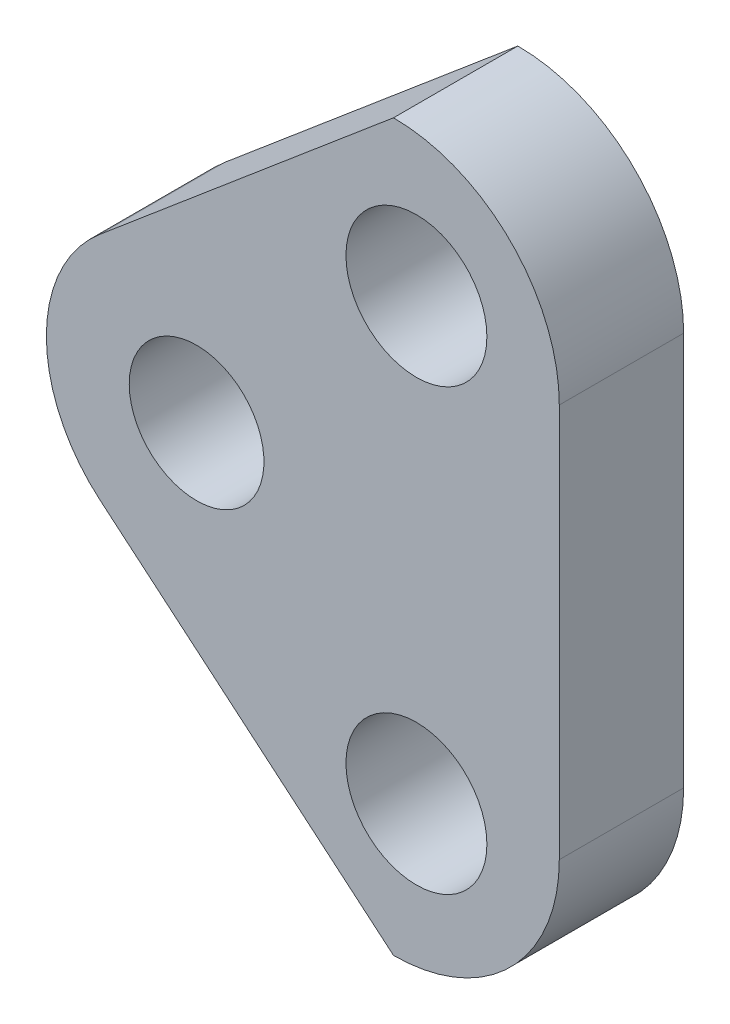
SolidWorks part; units mm, degrees
ref_plane "前视基准面" through (0, 0, 0) normal (0, 0, 1) x (1, 0, 0)
ref_plane "上视基准面" through (0, 0, 0) normal (0, 1, 0) x (1, 0, 0)
ref_plane "右视基准面" through (0, 0, 0) normal (1, 0, 0) x (0, 0, -1)
other "Configuration Table"
sketch "草图1" plane through (0, 0, 0) normal (0, 0, 1) x (1, 0, 0)
  line L1 (-9.5, -17.5) -> (9.5, -17.5)
  line L2 (-17.5, -9.5) -> (-17.5, 9.5)
  line L3 (-9.5, 17.5) -> (9.5, 17.5)
  line L4 (17.5, -9.5) -> (17.5, 9.5)
  line L5 (-17.5, -17.5) -> (17.5, 17.5) construction
  line L6 (-17.5, 17.5) -> (17.5, -17.5) construction
  circle A0 centre (0, 0) radius 15
  circle A1 centre (10.6066, 10.6066) radius 3.4
  circle A2 centre (10.6066, -10.6066) radius 3.4
  circle A3 centre (-10.6066, -10.6066) radius 3.4
  circle A4 centre (-10.6066, 10.6066) radius 3.4
  arc A5 (17.5, 9.5) -> (9.5, 17.5) centre (9.5, 9.5) ccw
  arc A6 (9.5, -17.5) -> (17.5, -9.5) centre (9.5, -9.5) ccw
  arc A7 (-9.5, -17.5) -> (-17.5, -9.5) centre (-9.5, -9.5) cw
  arc A8 (-17.5, 9.5) -> (-9.5, 17.5) centre (-9.5, 9.5) cw
  point P18 (0, 0)
  dimension "D1" = 30
  dimension "D2" = 6.8
  dimension "D6" = 8
  dimension "D3" = 35
  dimension "D4" = 35
  dimension "D5" = 4
extrude "凸台-拉伸1" add sketch "草图1" along normal blind 11 contours A4 A0 A3 A2 A1 | A8 L2 A7 L1 A6 L4 A5 L3 A4 A0 A1 A2 A3
sketch "草图2" plane through (0, 0, 0) normal (0, 0, -1) x (-1, 0, 0)
  circle A0 centre (10.6066, -10.6066) radius 3.4 construction
  circle A1 centre (-10.6066, -10.6066) radius 3.4 construction
  circle A2 centre (10.6066, 10.6066) radius 3.4 construction
  circle A3 centre (-10.6066, 10.6066) radius 3.4 construction
  circle A4 centre (10.6066, -10.6066) radius 3.4
  circle A5 centre (-10.6066, -10.6066) radius 3.4
  circle A6 centre (10.6066, 10.6066) radius 3.4
  circle A7 centre (-10.6066, 10.6066) radius 3.4
extrude "凸台-拉伸2" add sketch "草图2" against normal blind 3
sketch "草图3" plane through (0, 0, 11) normal (0, 0, 1) x (1, 0, 0)
  circle A0 centre (0, 0) radius 3.4
  dimension "D1" = 6.8
extrude "切除-拉伸1" cut sketch "草图3" against normal through all
sketch "草图4" plane through (0, 0, 0) normal (0, 0, -1) x (-1, 0, 0)
  circle A0 centre (0, 0) radius 6
  circle A1 centre (0, 0) radius 3.4 construction
  circle A2 centre (0, 0) radius 3.4
  dimension "D1" = 12
extrude "切除-拉伸2" cut sketch "草图4" against normal blind 5
sketch "草图6" plane through (0, 0, 0) normal (0, 0, -1) x (-1, 0, 0)
  line L0 (0, 17.5) -> (17.5, 0)
  line L1 (9.5, 17.5) -> (-9.5, 17.5) construction
  line L2 (17.5, -9.5) -> (17.5, 9.5) construction
  line L3 (17.5, 0) -> (0, -17.5)
  line L4 (9.5, -17.5) -> (-9.5, -17.5) construction
  line L9 (9.5, 17.5) -> (-9.5, 17.5)
  line L10 (-17.5, 9.5) -> (-17.5, -9.5)
  line L11 (-9.5, -17.5) -> (9.5, -17.5)
  line L12 (17.5, -9.5) -> (17.5, 9.5)
  line L13 (9.5, 17.5) -> (-9.5, 17.5)
  line L14 (-17.5, 9.5) -> (-17.5, -9.5)
  line L15 (-9.5, -17.5) -> (9.5, -17.5)
  line L16 (17.5, -9.5) -> (17.5, 9.5)
  arc A4 (17.5, 9.5) -> (9.5, 17.5) centre (9.5, 9.5) ccw
  arc A5 (-9.5, 17.5) -> (-17.5, 9.5) centre (-9.5, 9.5) ccw
  arc A6 (-17.5, -9.5) -> (-9.5, -17.5) centre (-9.5, -9.5) ccw
  arc A7 (9.5, -17.5) -> (17.5, -9.5) centre (9.5, -9.5) ccw
  arc A8 (17.5, 9.5) -> (9.5, 17.5) centre (9.5, 9.5) ccw
  arc A9 (-9.5, 17.5) -> (-17.5, 9.5) centre (-9.5, 9.5) ccw
  arc A10 (-17.5, -9.5) -> (-9.5, -17.5) centre (-9.5, -9.5) ccw
  arc A11 (9.5, -17.5) -> (17.5, -9.5) centre (9.5, -9.5) ccw
  arc M10 (17.5, 9.5) -> (9.5, 17.5) centre (9.5, 9.5) ccw
  line M11 (9.5, 17.5) -> (-9.5, 17.5)
  line M15 (-9.5, -17.5) -> (9.5, -17.5)
  arc M16 (9.5, -17.5) -> (17.5, -9.5) centre (9.5, -9.5) ccw
  line M17 (17.5, -9.5) -> (17.5, 9.5)
  dimension "D1" = 0
extrude "切除-拉伸3" cut sketch "草图6" against normal through all contours L0 M11 M17 M10 | L3 M17 M15 M16
sketch "草图7" plane through (0, 0, 11) normal (0, 0, 1) x (1, 0, 0)
  line L0 (17.5, -9.5) -> (17.5, 9.5) construction
  line L6 (0, -17.5) -> (9.5, -17.5)
  line L7 (-17.5, 0) -> (0, -17.5)
  line L8 (0, 17.5) -> (-17.5, 0)
  line L9 (9.5, 17.5) -> (0, 17.5)
  line L10 (17.5, -9.5) -> (17.5, 9.5)
  line L11 (0, -17.5) -> (9.5, -17.5)
  line L12 (-17.5, 0) -> (0, -17.5)
  line L13 (0, 17.5) -> (-17.5, 0)
  line L14 (9.5, 17.5) -> (0, 17.5)
  line L15 (17.5, -9.5) -> (17.5, 9.5)
  circle A0 centre (17.5, 0) radius 24.7487
  arc A3 (17.5, 9.5) -> (9.5, 17.5) centre (9.5, 9.5) ccw
  arc A4 (9.5, -17.5) -> (17.5, -9.5) centre (9.5, -9.5) ccw
  arc A5 (17.5, 9.5) -> (9.5, 17.5) centre (9.5, 9.5) ccw
  arc A6 (9.5, -17.5) -> (17.5, -9.5) centre (9.5, -9.5) ccw
  line M9 (-7.2226, -10.2774) -> (0, -17.5)
  line M15 (0, 17.5) -> (-7.2226, 10.2774)
  arc M16 (-7.2226, 10.2774) -> (-10.2774, 7.2226) centre (-10.6066, 10.6066) cw
  line M17 (-10.2774, 7.2226) -> (-17.5, 0)
  line M18 (-17.5, 0) -> (-10.2774, -7.2226)
  arc M19 (-10.2774, -7.2226) -> (-7.2226, -10.2774) centre (-10.6066, -10.6066) cw
  dimension "D1" = 0
extrude "切除-拉伸5" cut sketch "草图7" against normal through all contours A0 M15 M16 M17 M18 M19 M9 | L12 M19 | L13 M16
sketch "草图8" plane through (0, 0, 11) normal (0, 0, 1) x (1, 0, 0)
  line L3 (9.5, 17.5) -> (0, 17.5)
  line L4 (0, -17.5) -> (9.5, -17.5)
  line L5 (17.5, -9.5) -> (17.5, 9.5)
  line L6 (9.5, 17.5) -> (0, 17.5)
  line L7 (0, -17.5) -> (9.5, -17.5)
  line L8 (17.5, -9.5) -> (17.5, 9.5)
  arc A3 (0, 17.5) -> (0, -17.5) centre (17.5, 0) ccw
  arc A4 (9.5, -17.5) -> (17.5, -9.5) centre (9.5, -9.5) ccw
  arc A5 (17.5, 9.5) -> (9.5, 17.5) centre (9.5, 9.5) ccw
  arc A6 (0, 17.5) -> (0, -17.5) centre (17.5, 0) ccw
  arc A7 (9.5, -17.5) -> (17.5, -9.5) centre (9.5, -9.5) ccw
  arc A8 (17.5, 9.5) -> (9.5, 17.5) centre (9.5, 9.5) ccw
  dimension "D1" = 0
extrude "切除-拉伸6" cut sketch "草图8" against normal blind 5
sketch "草图9" plane through (0, 0, 0) normal (0, 0, -1) x (-1, 0, 0)
  line L3 (0, 17.5) -> (-9.5, 17.5)
  line L4 (-17.5, 9.5) -> (-17.5, -9.5)
  line L5 (-9.5, -17.5) -> (0, -17.5)
  line L6 (0, 17.5) -> (-9.5, 17.5)
  line L7 (-17.5, 9.5) -> (-17.5, -9.5)
  line L8 (-9.5, -17.5) -> (0, -17.5)
  circle A0 centre (0, 0) radius 6 construction
  circle A1 centre (0, 0) radius 6
  circle A2 centre (-10.6066, 10.6066) radius 3.4 construction
  arc A3 (0, -17.5) -> (0, 17.5) centre (-17.5, 0) ccw
  arc A4 (-9.5, 17.5) -> (-17.5, 9.5) centre (-9.5, 9.5) ccw
  arc A5 (-17.5, -9.5) -> (-9.5, -17.5) centre (-9.5, -9.5) ccw
  arc A6 (0, -17.5) -> (0, 17.5) centre (-17.5, 0) ccw
  arc A7 (-9.5, 17.5) -> (-17.5, 9.5) centre (-9.5, 9.5) ccw
  arc A8 (-17.5, -9.5) -> (-9.5, -17.5) centre (-9.5, -9.5) ccw
  circle A9 centre (-10.6066, 10.6066) radius 3.4
  circle A10 centre (-10.6066, -10.6066) radius 3.4 construction
  circle A11 centre (-10.6066, -10.6066) radius 3.4
  dimension "D1" = 0
extrude "切除-拉伸7" cut sketch "草图9" against normal blind 10 contours A9 | A1 | A11
sketch "草图10" plane through (0, 0, 6) normal (0, 0, 1) x (1, 0, 0)
  line L0 (9.5, 17.5) -> (-4.6745, 5.5401)
  line L1 (-4.6745, -5.5401) -> (9.5, -17.5)
  line L5 (9.5, 17.5) -> (0, 17.5)
  line L6 (0, -17.5) -> (9.5, -17.5)
  line L7 (17.5, -9.5) -> (17.5, 9.5)
  line L8 (9.5, 17.5) -> (0, 17.5)
  line L9 (0, -17.5) -> (9.5, -17.5)
  line L10 (17.5, -9.5) -> (17.5, 9.5)
  circle A0 centre (0, 0) radius 7.2487
  arc A4 (17.5, 9.5) -> (9.5, 17.5) centre (9.5, 9.5) ccw
  arc A5 (0, 17.5) -> (0, -17.5) centre (17.5, 0) ccw
  arc A6 (9.5, -17.5) -> (17.5, -9.5) centre (9.5, -9.5) ccw
  arc A7 (17.5, 9.5) -> (9.5, 17.5) centre (9.5, 9.5) ccw
  arc A8 (0, 17.5) -> (0, -17.5) centre (17.5, 0) ccw
  arc A9 (9.5, -17.5) -> (17.5, -9.5) centre (9.5, -9.5) ccw
  line M13 (9.5, 17.5) -> (0, 17.5)
  arc M14 (0, 17.5) -> (0, -17.5) centre (17.5, 0) ccw
  line M15 (0, -17.5) -> (9.5, -17.5)
  dimension "D1" = 0
extrude "切除-拉伸8" cut sketch "草图10" against normal blind 10 contours A0 L0 M13 M14 | A0 L1 M14 M15
sketch "草图11" plane through (0, 0, 0) normal (0, 0, -1) x (-1, 0, 0)
  circle A0 centre (0, 0) radius 3.25
  circle A1 centre (0, 0) radius 6 construction
  circle A2 centre (0, 0) radius 6
  dimension "D1" = 6.5
extrude "凸台-拉伸3" add sketch "草图11" against normal through all
move or copy body "实体-移动/复制1" [suppressed] bodies to move or copy 117 parameters "D1"=0, "D2"=0, "D3"=0
move or copy body "实体-移动/复制2" [suppressed] bodies to move or copy 118 parameters "D1"=0, "D2"=0, "D3"=0
